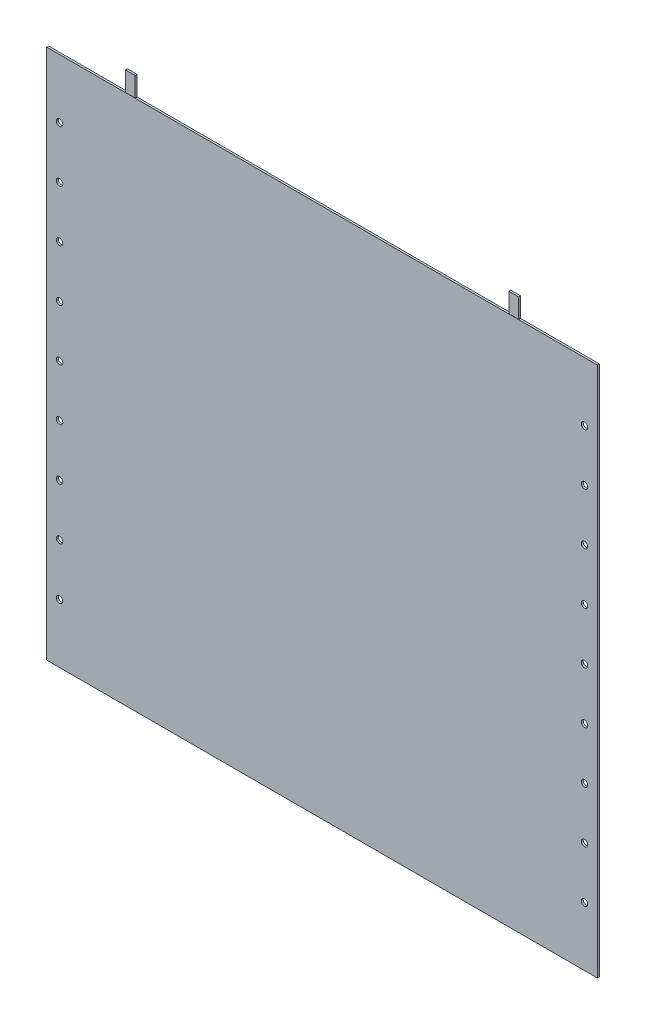
SolidWorks part; units mm, degrees
ref_plane "Front Plane" through (0, 0, 0) normal (0, 0, 1) x (1, 0, 0)
ref_plane "Top Plane" through (0, 0, 0) normal (0, 1, 0) x (1, 0, 0)
ref_plane "Right Plane" through (0, 0, 0) normal (1, 0, 0) x (0, 0, -1)
sketch "Sketch1" plane through (0, 0, 0) normal (0, 0, 1) x (1, 0, 0)
  line L0 (0, 135) -> (0, -135) construction
  line L1 (-140, 135) -> (-100, 135)
  line L2 (-140, 135) -> (-140, -135)
  line L3 (-140, -135) -> (140, -135)
  line L4 (140, 135) -> (140, -135)
  line L5 (-140, 135) -> (140, -135) construction
  line L6 (-140, -135) -> (140, 135) construction
  line L7 (-127, 135) -> (-127, -135) construction
  line L8 (127, 135) -> (127, -135) construction
  line L9 (-95, 135) -> (95, 135)
  line L11 (-100, 135) -> (-100, 145)
  line L12 (-100, 145) -> (-95, 145)
  line L13 (-95, 135) -> (-95, 145)
  line L15 (95, 135) -> (95, 145)
  line L16 (95, 145) -> (100, 145)
  line L17 (100, 135) -> (100, 145)
  line L18 (100, 135) -> (140, 135)
  circle A1 centre (-133.5, 0) radius 1.65
  circle A7 centre (-133.5, 26.25) radius 1.65
  circle A8 centre (-133.5, 52.5) radius 1.65
  circle A9 centre (-133.5, 78.75) radius 1.65
  circle A10 centre (-133.5, 105) radius 1.65
  circle A11 centre (-133.5, -26.25) radius 1.65
  circle A12 centre (-133.5, -52.5) radius 1.65
  circle A13 centre (-133.5, -78.75) radius 1.65
  circle A14 centre (-133.5, -105) radius 1.65
  circle A15 centre (133.5, -105) radius 1.65
  circle A16 centre (133.5, -78.75) radius 1.65
  circle A17 centre (133.5, -52.5) radius 1.65
  circle A18 centre (133.5, -26.25) radius 1.65
  circle A19 centre (133.5, 105) radius 1.65
  circle A20 centre (133.5, 78.75) radius 1.65
  circle A21 centre (133.5, 52.5) radius 1.65
  circle A22 centre (133.5, 26.25) radius 1.65
  circle A23 centre (133.5, 0) radius 1.65
  point P0 (0, 0)
  dimension "D5" = 5
  dimension "D6" = 5
  dimension "D7" = 40
  dimension "D8" = 3.3
  dimension "D9" = 40
  dimension "D12" = 6.5
  dimension "D1" = 280
  dimension "D2" = 270
  dimension "D13" = 5
  dimension "D14" = 10
  dimension "D15" = 5
  dimension "D16" = 10
  dimension "D3" = 127
  dimension "D4" = 127
extrude "Boss-Extrude1" add sketch "Sketch1" along normal blind 1
sketch "Sketch2" plane through (0, 0, 1) normal (0, 0, 1) x (1, 0, 0)
  line L0 (-95, 135) -> (-95, 145) construction
  line L1 (-100, 135) -> (-95, 135)
  line L2 (-100, 135) -> (-100, 135.1)
  line L3 (-100, 135.1) -> (-95, 135.1)
  line L4 (-95, 135) -> (-95, 135.1)
  line L6 (100, 135) -> (100, 145) construction
  line L7 (95, 135) -> (100, 135)
  line L8 (95, 135) -> (95, 135.1)
  line L9 (95, 135.1) -> (100, 135.1)
  line L10 (100, 135) -> (100, 135.1)
  dimension "D1" = 0.1
  dimension "D2" = 0.1
extrude "Cut-Extrude1" cut sketch "Sketch2" against normal blind 0.1
